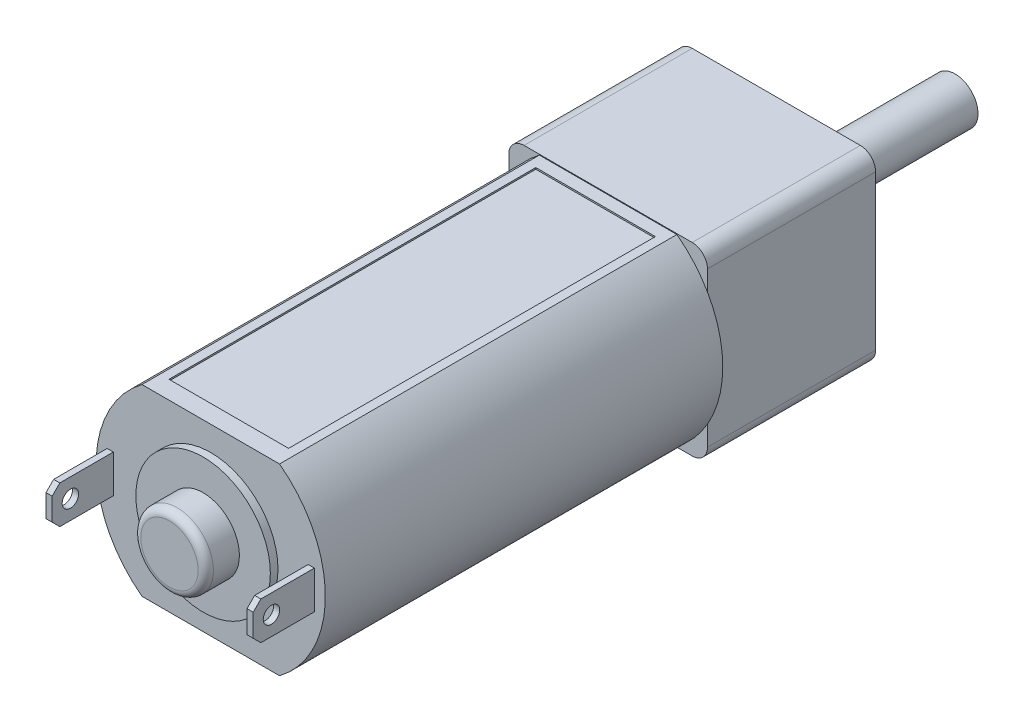
SolidWorks part; units mm, degrees
ref_plane "Alzado" through (0, 0, 0) normal (0, 0, 1) x (1, 0, 0)
ref_plane "Planta" through (0, 0, 0) normal (0, 1, 0) x (1, 0, 0)
ref_plane "Vista lateral" through (0, 0, 0) normal (1, 0, 0) x (0, 0, -1)
sketch "Croquis1" plane through (0, 0, 0) normal (0, 0, 1) x (1, 0, 0)
  line L0 (6.5, -6.05) -> (6.5, 6.05)
  line L1 (6.5, 6.05) -> (-6.5, 6.05)
  line L2 (-6.5, 6.05) -> (-6.5, -6.05)
  line L3 (-6.5, -6.05) -> (6.5, -6.05)
extrude "Saliente-Extruir1" add sketch "Croquis1" against normal blind 11
sketch "Croquis2" plane through (0, 0, 0) normal (0, 0, 1) x (1, 0, 0)
  line L0 (-4.5, 6) -> (4.5, 6)
  line L1 (4.5, -6) -> (-4.5, -6)
  arc A0 (4.5, 6) -> (4.5, -6) centre (0, 0) cw
  arc A1 (-4.5, -6) -> (-4.5, 6) centre (0, 0) cw
extrude "Saliente-Extruir2" add sketch "Croquis2" along normal blind 26
sketch "Croquis3" plane through (0, 0, -11) normal (0, 0, -1) x (-1, 0, 0)
  circle A0 centre (0, 0) radius 1.6
extrude "Saliente-Extruir3" add sketch "Croquis3" along normal blind 0.2
sketch "Croquis4" plane through (0, 0, -11.2) normal (0, 0, -1) x (-1, 0, 0)
  circle A0 centre (0, 0) radius 1.5
extrude "Saliente-Extruir4" add sketch "Croquis4" along normal blind 11.5
sketch "Croquis5" plane through (0, 0, -22.7) normal (0, 0, -1) x (-1, 0, 0)
  line L0 (1.0722, -1.049) -> (-1.0722, -1.049)
  arc A0 (-1.0722, -1.049) -> (1.0722, -1.049) centre (0, 0) ccw
extrude "Cortar-Extruir1" cut sketch "Croquis5" against normal blind 10
sketch "Croquis6" plane through (0, 0, 26) normal (0, 0, 1) x (1, 0, 0)
  line L0 (-6.7785, 1.2397) -> (-6.3742, 1.2397)
  line L1 (-6.3742, 1.2397) -> (-6.3742, -1.2397)
  line L2 (-6.3742, -1.2397) -> (-6.7785, -1.2397)
  line L3 (-6.7785, -1.2397) -> (-6.7785, 1.2397)
extrude "Saliente-Extruir5" add sketch "Croquis6" along normal blind 4
sketch "Croquis7" plane through (0, 0, 26) normal (0, 0, 1) x (1, 0, 0)
  line L0 (6.7785, -1.2397) -> (6.3742, -1.2397)
  line L1 (6.3742, -1.2397) -> (6.3742, 1.2397)
  line L2 (6.3742, 1.2397) -> (6.7785, 1.2397)
  line L3 (6.7785, 1.2397) -> (6.7785, -1.2397)
extrude "Saliente-Extruir6" add sketch "Croquis7" along normal blind 4
sketch "Croquis8" plane through (0, 6, 0) normal (0, 1, 0) x (-1, 0, 0)
  line L0 (3.9129, 0.8199) -> (3.9129, 24.8192)
  line L1 (3.9129, 24.8192) -> (-3.9129, 24.8192)
  line L2 (-3.9129, 24.8192) -> (-3.9129, 0.8199)
  line L3 (-3.9129, 0.8199) -> (3.9129, 0.8199)
extrude "Cortar-Extruir2" cut sketch "Croquis8" against normal blind 0.1
sketch "Croquis9" plane through (0, 0, 0) normal (0, 1, 0) x (1, 0, 0)
  line L0 (4.4, -26) -> (0, -26)
  line L1 (0, -26) -> (0, -28.7)
  line L2 (0, -28.7) -> (2.375, -28.7)
  line L3 (2.375, -28.7) -> (2.375, -26.5)
  line L4 (2.375, -26.5) -> (4.4, -26.5)
  line L5 (4.4, -26.5) -> (4.4, -26)
  line L6 (0, -26) -> (0, -28.7) construction
revolve "Revolución1" add sketch "Croquis9" angle 360 about L6
ref_plane "Plano1" through (0, -4.05, 0) normal (0, 1, 0) x (1, 0, 0)
sketch "Croquis10" plane through (0, -4.05, 0) normal (0, 1, 0) x (1, 0, 0)
  line L0 (-3.35, 11) -> (-4.5, 11)
  line L1 (-4.5, 11) -> (-4.5, 10.9)
  line L2 (-4.5, 10.9) -> (-3.35, 10.9)
  line L3 (-3.35, 10.9) -> (-3.35, 11)
  line L4 (-4.5, 11) -> (-4.5, 10.9) construction
revolve "Cortar-Revolución1" cut sketch "Croquis10" angle 360 about L4
ref_plane "Plano2" through (0, 4.05, 0) normal (0, 1, 0) x (1, 0, 0)
sketch "Croquis11" plane through (0, 4.05, 0) normal (0, 1, 0) x (1, 0, 0)
  line L0 (5.65, 11) -> (4.5, 11)
  line L1 (4.5, 11) -> (4.5, 10.9)
  line L2 (4.5, 10.9) -> (5.65, 10.9)
  line L3 (5.65, 10.9) -> (5.65, 11)
  line L4 (4.5, 11) -> (4.5, 10.9) construction
revolve "Cortar-Revolución2" cut sketch "Croquis11" angle 360 about L4
hole_wizard "Taladro1" positions "Croquis13" profile "Croquis12" legacy
sketch "Croquis13" plane through (-6.3742, 0, 0) normal (1, 0, 0) x (0, 0, -1)
  point P0 (-28.8068, 0)
sketch "Croquis12" plane through (-6.3742, 0, 28.8068) normal (0, 1, 0) x (0, 0, -1)
  line L0 (0, 0) -> (0, 1.1258)
  line L1 (0, 1.1258) -> (0.5386, 1.1258)
  line L2 (0.5386, 1.1258) -> (0.5386, 0)
  line L3 (0.5386, 0) -> (0, 0)
  line L4 (0, 110) -> (0, -10) construction
  dimension "Diámetro" = 1.0772
  dimension "Profundidad" = 1.1258
hole_wizard "Taladro2" positions "Croquis15" profile "Croquis14" legacy
sketch "Croquis15" plane through (6.3742, 0, 0) normal (-1, 0, 0) x (0, 0, 1)
  point P0 (28.8068, 0)
sketch "Croquis14" plane through (6.3742, 0, 28.8068) normal (0, 1, 0) x (0, 0, 1)
  line L0 (0, 0) -> (0, 1.1258)
  line L1 (0, 1.1258) -> (0.5386, 1.1258)
  line L2 (0.5386, 1.1258) -> (0.5386, 0)
  line L3 (0.5386, 0) -> (0, 0)
  line L4 (0, 110) -> (0, -10) construction
  dimension "Diámetro" = 1.0772
  dimension "Profundidad" = 1.1258
hole_wizard "Diámetro de taladro Ø2.0 (2)1" positions "Croquis17" profile "Croquis16" hole size "Ø2.0" standard "Ansi Metric"
sketch "Croquis17" plane through (0, 0, -11) normal (0, 0, -1) x (-1, 0, 0)
  point P0 (0, 4.375)
  point P1 (0, -4.375)
sketch "Croquis16" plane through (0, 4.375, -11) normal (1, 0, 0) x (0, 1, 0)
  line L0 (0, 0) -> (0, 5.6009)
  line L1 (0, 5.6009) -> (1, 5)
  line L2 (1, 5) -> (1, 0)
  line L5 (1, 0) -> (0, 0)
  line L10 (0, 5.6009) -> (-1, 5) construction
  line L11 (0, -6.35) -> (0, 107.95) construction
  dimension "Diámetro de taladro" = 2
  dimension "Profundidad de taladro" = 5
  dimension "Ángulo de perforador" = 118
chamfer "Chaflán1" distance 0.5 angle 45 4 edges at (6.5763, 1.2397, 30) (-6.5763, 1.2397, 30) (6.5763, -1.2397, 30) (-6.5763, -1.2397, 30)
fillet "Redondeo1" radius 0.5 1 edges at (2.375, 0, 28.7)
fillet "Redondeo2" radius 1 4 edges at (-6.5, 6.05, -5.5) (-6.5, -6.05, -5.5) (6.5, 6.05, -5.5) (6.5, -6.05, -5.5)
